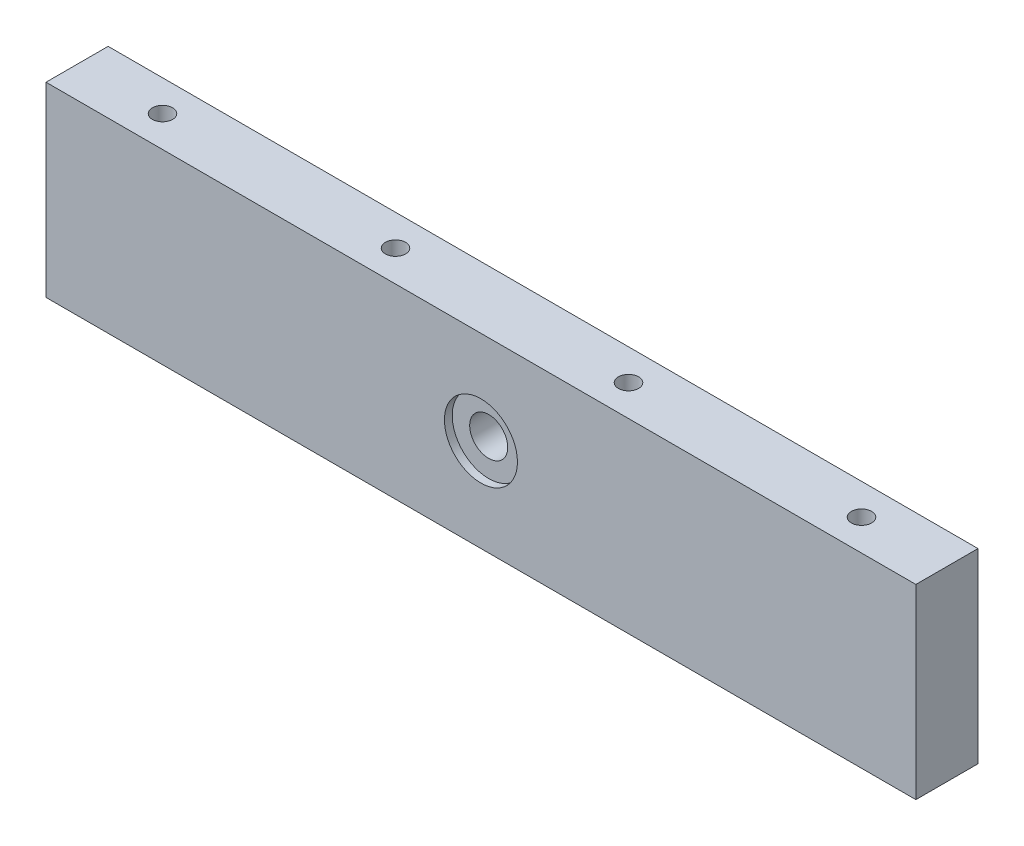
SolidWorks part; units mm, degrees
ref_plane "前视基准面" through (0, 0, 0) normal (0, 0, 1) x (1, 0, 0)
ref_plane "上视基准面" through (0, 0, 0) normal (0, 1, 0) x (1, 0, 0)
ref_plane "右视基准面" through (0, 0, 0) normal (1, 0, 0) x (0, 0, -1)
sketch "草图1" plane through (0, 0, 0) normal (0, 0, 1) x (1, 0, 0)
  line L1 (-56, -12) -> (56, -12)
  line L2 (-56, -12) -> (-56, 12)
  line L3 (-56, 12) -> (56, 12)
  line L4 (56, -12) -> (56, 12)
  line L5 (-56, -12) -> (56, 12) construction
  line L6 (-56, 12) -> (56, -12) construction
  point P0 (0, 0)
  dimension "D1" = 112
  dimension "D2" = 24
extrude "凸台-拉伸1" add sketch "草图1" along normal blind 8
sketch "草图2" plane through (0, 12, 0) normal (0, 1, 0) x (1, 0, 0)
  line L0 (-56, -4) -> (56, -4) construction
  line L1 (-56, -8) -> (-56, 0) construction
  line L2 (56, -8) -> (56, 0) construction
  line L3 (0, 0) -> (0, -8) construction
  line L4 (56, 0) -> (-56, 0) construction
  line L5 (56, -8) -> (-56, -8) construction
  circle A0 centre (-15, -4) radius 1.3
  circle A1 centre (-45, -4) radius 1.3
  circle A2 centre (45, -4) radius 1.3
  circle A3 centre (15, -4) radius 1.3
  dimension "D1" = 2.6
  dimension "D2" = 2.6
  dimension "D3" = 15
  dimension "D4" = 30
extrude "切除-拉伸1" cut sketch "草图2" against normal blind 30
sketch "草图3" plane through (0, 0, 0) normal (0, 0, -1) x (-1, 0, 0)
  circle A0 centre (0, 0) radius 2.45
  dimension "D1" = 4.9
extrude "切除-拉伸2" cut sketch "草图3" against normal blind 30
sketch "草图4" plane through (0, 0, 0) normal (0, 0, -1) x (-1, 0, 0)
  line L1 (4.0522, -1.9646) -> (3.7275, 2.527)
  line L2 (3.7275, 2.527) -> (-0.3247, 4.4916)
  line L3 (-0.3247, 4.4916) -> (-4.0522, 1.9646)
  line L4 (-4.0522, 1.9646) -> (-3.7275, -2.527)
  line L5 (-3.7275, -2.527) -> (0.3247, -4.4916)
  line L6 (0.3247, -4.4916) -> (4.0522, -1.9646)
  circle A0 centre (0, 0) radius 3.9 construction
extrude "切除-拉伸3" cut sketch "草图4" against normal blind 2
sketch "草图5" plane through (0, 0, 8) normal (0, 0, 1) x (1, 0, 0)
  circle A0 centre (0, 0) radius 4.7
  dimension "D1" = 9.4
extrude "切除-拉伸4" cut sketch "草图5" against normal blind 1
